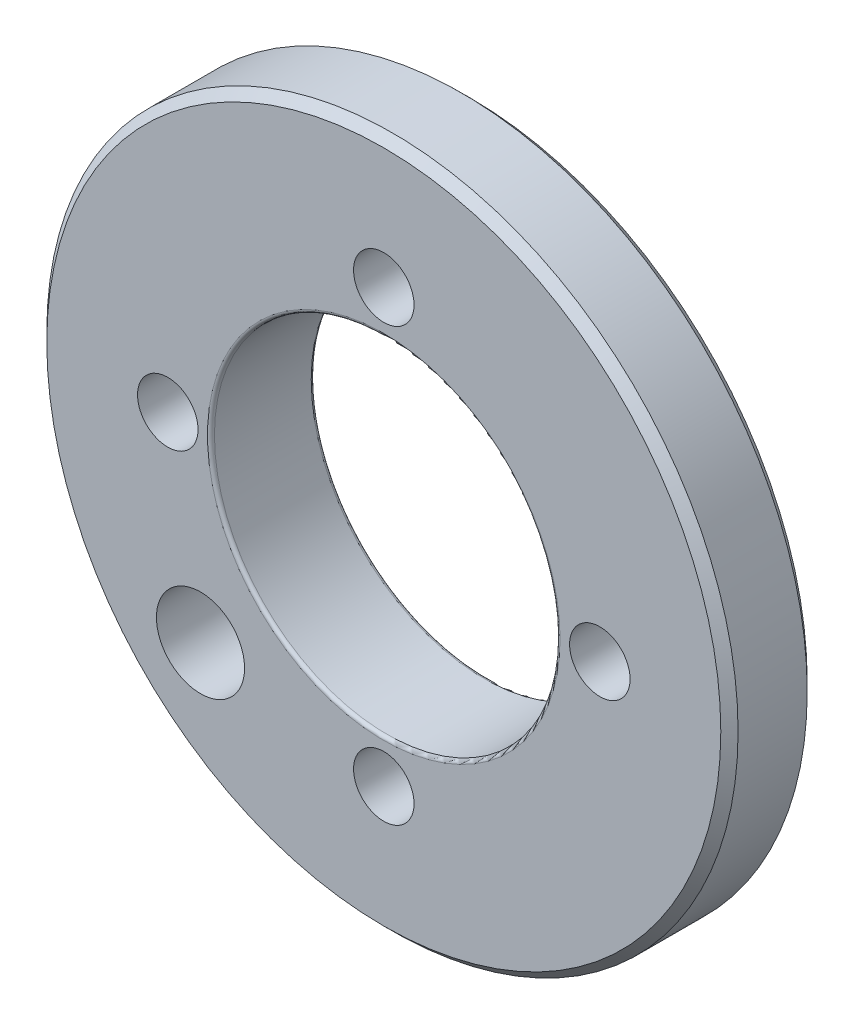
SolidWorks part; units mm, degrees
ref_plane "Front Plane" through (0, 0, 0) normal (0, 0, 1) x (1, 0, 0)
ref_plane "Top Plane" through (0, 0, 0) normal (0, 1, 0) x (1, 0, 0)
ref_plane "Right Plane" through (0, 0, 0) normal (1, 0, 0) x (0, 0, -1)
sketch "Sketch1" plane through (0, 0, 0) normal (0, 0, 1) x (1, 0, 0)
  line L0 (0, 0) -> (8.8388, 8.8388) construction
  line L1 (0, 0) -> (12.5, 0) construction
  circle A0 centre (0, 0) radius 16.5
  circle A1 centre (0, 0) radius 9.5
  circle A2 centre (0, 0) radius 12.5 construction
  circle A3 centre (12.5, 0) radius 1.75
  circle A4 centre (0, -12.5) radius 1.75
  circle A5 centre (-12.5, 0) radius 1.75
  circle A6 centre (0, 12.5) radius 1.75
  point P16 (0, 0)
  dimension "D1" = 33
  dimension "D2" = 19
  dimension "D3" = 25
  dimension "D4" = 3.5
  dimension "D7" = 45
  dimension "D5" = 4
extrude "Boss-Extrude1" add sketch "Sketch1" along normal blind 6
sketch "Sketch2" plane through (0, 0, 6) normal (0, 0, 1) x (1, 0, 0)
  circle A1 centre (12.5, 0) radius 2.8
  dimension "D1" = 5.6
extrude "Cut-Extrude1" cut sketch "Sketch2" against normal blind 3
sketch "Sketch3" plane through (0, 0, 6) normal (0, 0, 1) x (1, 0, 0)
  line L0 (0, 0) -> (-13.31, -14.928) construction
  line L1 (0, 0) -> (-20, 0) construction
  circle A0 centre (12.5, 0) radius 1.75
  circle A1 centre (0, 0) radius 20
  circle A3 centre (12.5, 0) radius 1.75 construction
  circle A4 centre (0, -12.5) radius 2.8
  circle A5 centre (-12.5, 0) radius 2.8
  circle A6 centre (0, 12.5) radius 2.8
  point P17 (0, 0)
  dimension "D2" = 40
extrude "Boss-Extrude2" add sketch "Sketch3" against normal blind 5
sketch "Sketch6" plane through (0, 0, 6) normal (0, 0, 1) x (1, 0, 0)
  line L0 (0, 0) -> (-12.5, 0) construction
  line L1 (0, 0) -> (-10.6066, -10.6066) construction
  circle A0 centre (0, 0) radius 15 construction
  circle A1 centre (0, 0) radius 20 construction
  circle A2 centre (-10.6066, -10.6066) radius 2.55
  dimension "D1" = 5
  dimension "D3" = 5.1
  dimension "D2" = 45
extrude "Cut-Extrude3" cut sketch "Sketch6" against normal blind 5
sketch "Sketch7" plane through (0, 0, 6) normal (0, 0, 1) x (1, 0, 0)
  circle A0 centre (0, 0) radius 10
  dimension "D1" = 20
extrude "Cut-Extrude4" cut sketch "Sketch7" against normal through all
fillet "Fillet1" radius 0.2 2 edges at (10, 0, 6) (10, 0, 0)
chamfer "Chamfer1" distance 0.5 angle 45 2 edges at (20, 0, 1) (20, 0, 6)
